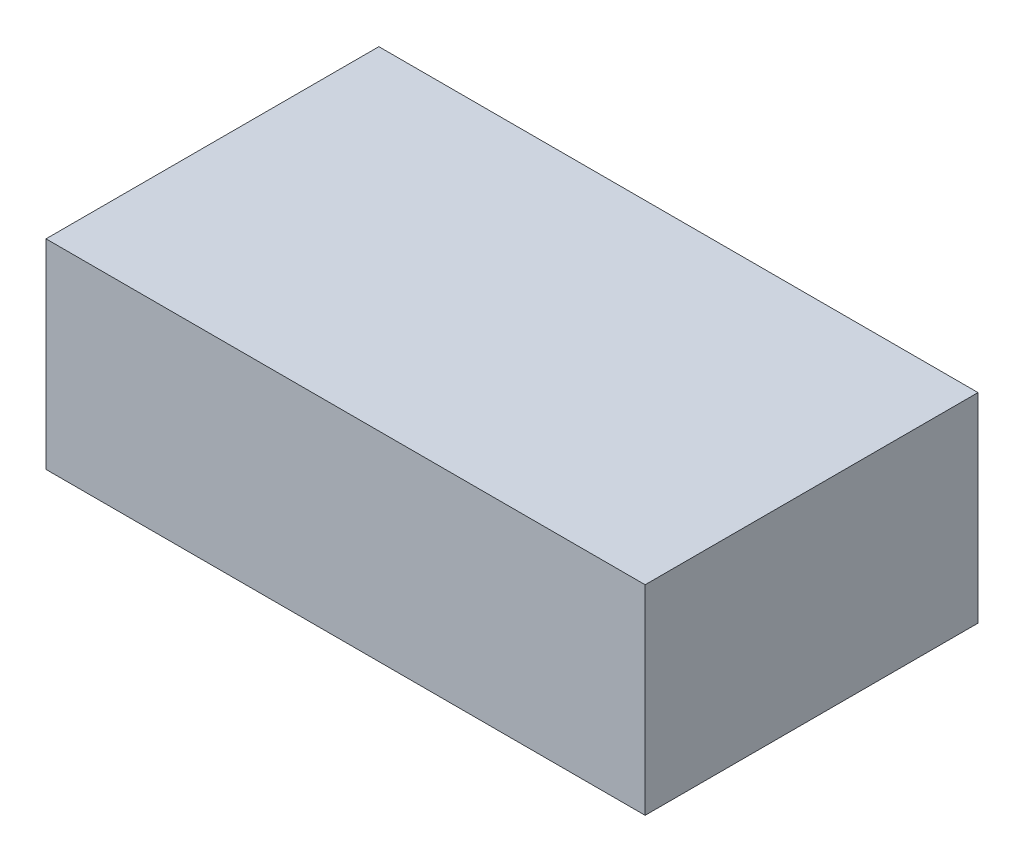
SolidWorks part; units mm, degrees
ref_plane "Спереди" through (0, 0, 0) normal (0, 0, 1) x (1, 0, 0)
ref_plane "Сверху" through (0, 0, 0) normal (0, 1, 0) x (1, 0, 0)
ref_plane "Справа" through (0, 0, 0) normal (1, 0, 0) x (0, 0, -1)
sketch "Эскиз2" plane through (0, 0, 0) normal (0, 0, 1) x (1, 0, 0)
  line L1 (-13.5, -4.5) -> (13.5, -4.5)
  line L2 (-13.5, -4.5) -> (-13.5, 4.5)
  line L3 (-13.5, 4.5) -> (13.5, 4.5)
  line L4 (13.5, -4.5) -> (13.5, 4.5)
  line L5 (-13.5, -4.5) -> (13.5, 4.5) construction
  line L6 (-13.5, 4.5) -> (13.5, -4.5) construction
  point P0 (0, 0)
  dimension "D1" = 27
  dimension "D2" = 9
extrude "Бобышка-Вытянуть1" add sketch "Эскиз2" along normal blind 15
